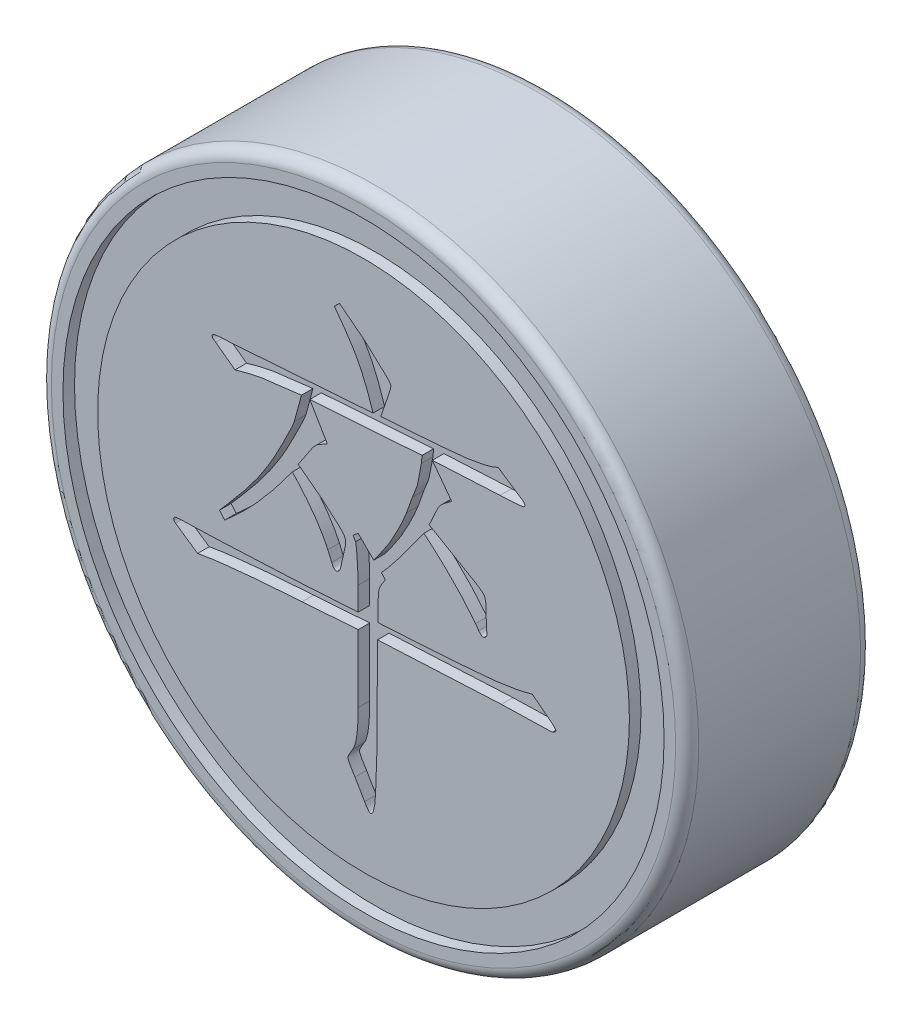
SolidWorks part; units mm, degrees
ref_plane "前视基准面" through (0, 0, 0) normal (0, 0, 1) x (1, 0, 0)
ref_plane "上视基准面" through (0, 0, 0) normal (0, 1, 0) x (1, 0, 0)
ref_plane "右视基准面" through (0, 0, 0) normal (1, 0, 0) x (0, 0, -1)
sketch "草图1" plane through (0, 0, 0) normal (0, 0, 1) x (1, 0, 0)
  circle A0 centre (0, 0) radius 14
extrude "凸台-拉伸1" add sketch "草图1" along normal blind 8
sketch "草图2" plane through (0, 0, 8) normal (0, 0, 1) x (1, 0, 0)
  circle A0 centre (0, 0) radius 13
  circle A1 centre (0, 0) radius 11.5
extrude "切除-拉伸1" cut sketch "草图2" against normal blind 0.5
sketch "草图3" plane through (0, 0, 0) normal (0, 0, -1) x (-1, 0, 0)
  circle A0 centre (0, 0) radius 5.1
extrude "切除-拉伸2" cut sketch "草图3" against normal blind 5
chamfer "倒角1" distance 0.5 angle 45 1 edges at (-5.1, 0, 0)
fillet "圆角1" radius 0.5 2 edges at (14, 0, 8) (14, 0, 0)
sketch "草图4" plane through (0, 0, 8) normal (0, 0, 1) x (1, 0, 0)
  text T0 "卒" font "汉仪长仿宋体" height 13
extrude "切除-拉伸3" cut sketch "草图4" against normal blind 0.5
